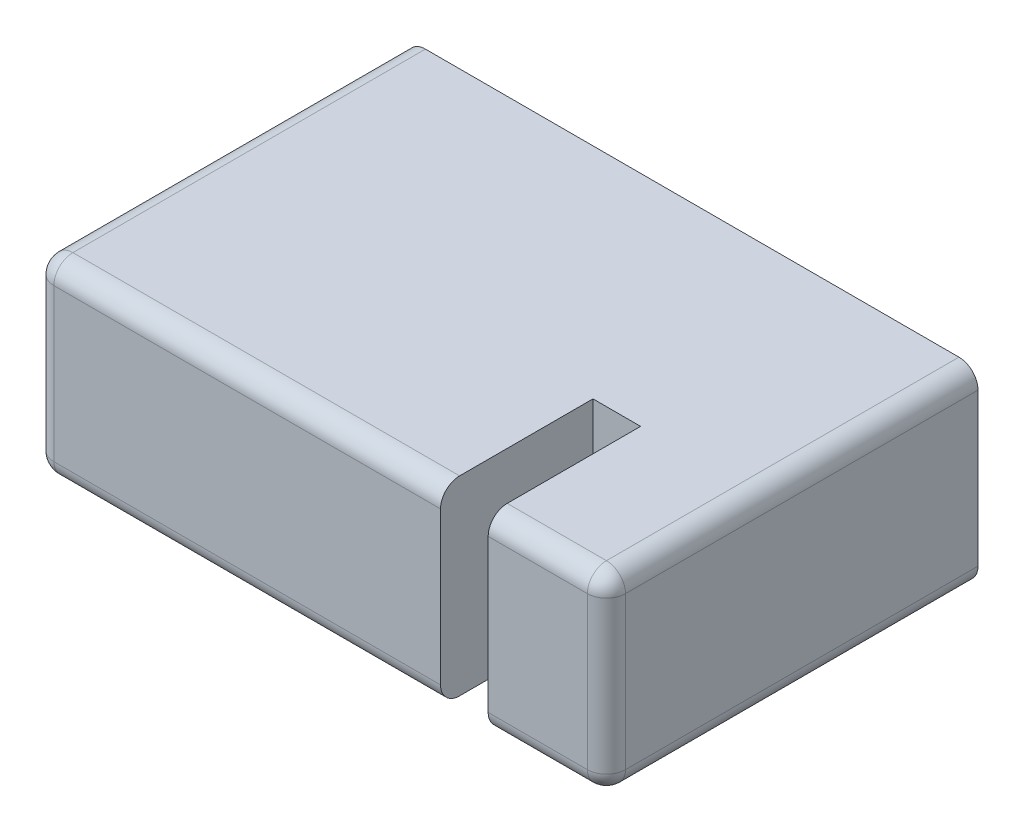
SolidWorks part; units mm, degrees
material "ABS"
ref_plane "Front" through (0, 0, 0) normal (0, 0, 1) x (1, 0, 0)
ref_plane "Top" through (0, 0, 0) normal (0, 1, 0) x (1, 0, 0)
ref_plane "Right" through (0, 0, 0) normal (1, 0, 0) x (0, 0, -1)
sketch "Sketch1" plane through (0, 0, 0) normal (0, 0, 1) x (1, 0, 0)
  line L1 (0, 0) -> (76.2, 0)
  line L2 (0, 0) -> (0, 25.4)
  line L3 (0, 25.4) -> (76.2, 25.4)
  line L4 (76.2, 0) -> (76.2, 25.4)
extrude "Extrude1" add sketch "Sketch1" along normal blind 49.53
sketch "Sketch2" plane through (0, 0, 0) normal (0, -1, 0) x (1, 0, 0)
  line L0 (0, 49.53) -> (76.2, 49.53) construction
  line L1 (54.0859, 49.53) -> (60.4359, 49.53)
  line L2 (54.0859, 49.53) -> (54.0859, 29.21)
  line L3 (54.0859, 29.21) -> (60.4359, 29.21)
  line L4 (60.4359, 49.53) -> (60.4359, 29.21)
extrude "Extrude2" cut sketch "Sketch2" against normal through all
fillet "Fillet1" radius 2.54 10 edges at (0, 25.4, 24.765) (27.0429, 25.4, 49.53) (0, 12.7, 49.53) (0, 0, 24.765) (27.0429, 0, 49.53) (76.2, 0, 24.765) (76.2, 25.4, 24.765) (76.2, 12.7, 49.53) (68.3179, 25.4, 49.53) (68.3179, 0, 49.53)
hole_wizard "#10-32 Tapped Hole1" positions "3DSketch1" profile "Sketch3" tap size "#10-32" standard "Superior"
sketch3d "3DSketch1"
  point P0 (66.04, 12.7, 0)
  point P2 (19.05, 12.7, 0)
sketch "Sketch3" plane through (66.04, 12.7, 0) normal (1, 0, 0) x (0, 1, 0)
  line L0 (0, 0) -> (0, 14.8277)
  line L1 (0, 14.8277) -> (2.0193, 13.6144)
  line L2 (2.0193, 13.6144) -> (2.0193, 0)
  line L5 (2.0193, 0) -> (0, 0)
  line L10 (0, 14.8277) -> (-2.0193, 13.6144) construction
  line L11 (0, -6.35) -> (0, 107.95) construction
  dimension "Tap Drill Dia." = 4.0386
  dimension "Tap Drill Depth" = 13.6144
  dimension "Drill Angle" = 118
cosmetic thread "Hole Thread1" parameters "D1"=9.652, "D2"=4.826
cosmetic thread "Hole Thread2" parameters "D1"=9.652, "D2"=4.826
